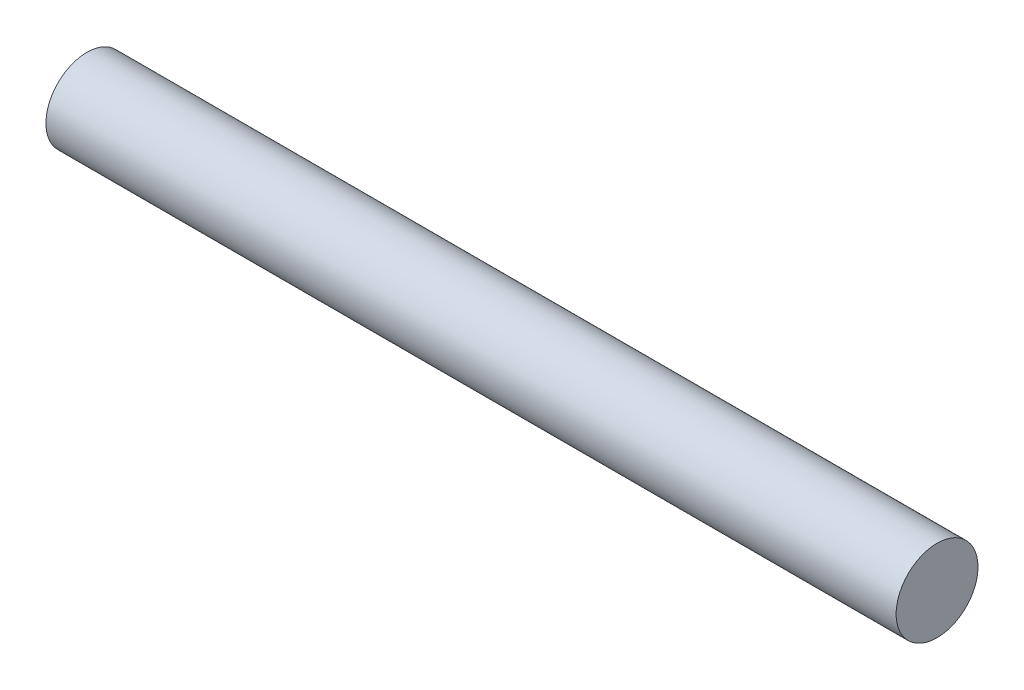
SolidWorks part; units mm, degrees
ref_plane "Front" through (0, 0, 0) normal (0, 0, 1) x (1, 0, 0)
ref_plane "Top" through (0, 0, 0) normal (0, 1, 0) x (1, 0, 0)
ref_plane "Right" through (0, 0, 0) normal (1, 0, 0) x (0, 0, -1)
sketch "Sketch1" plane through (0, 0, 0) normal (1, 0, 0) x (0, 0, -1)
  circle A0 centre (0, 0) radius 0.1651
  dimension "D1" = 0.3302
extrude "Boss-Extrude1" add sketch "Sketch1" along normal blind 3.429
